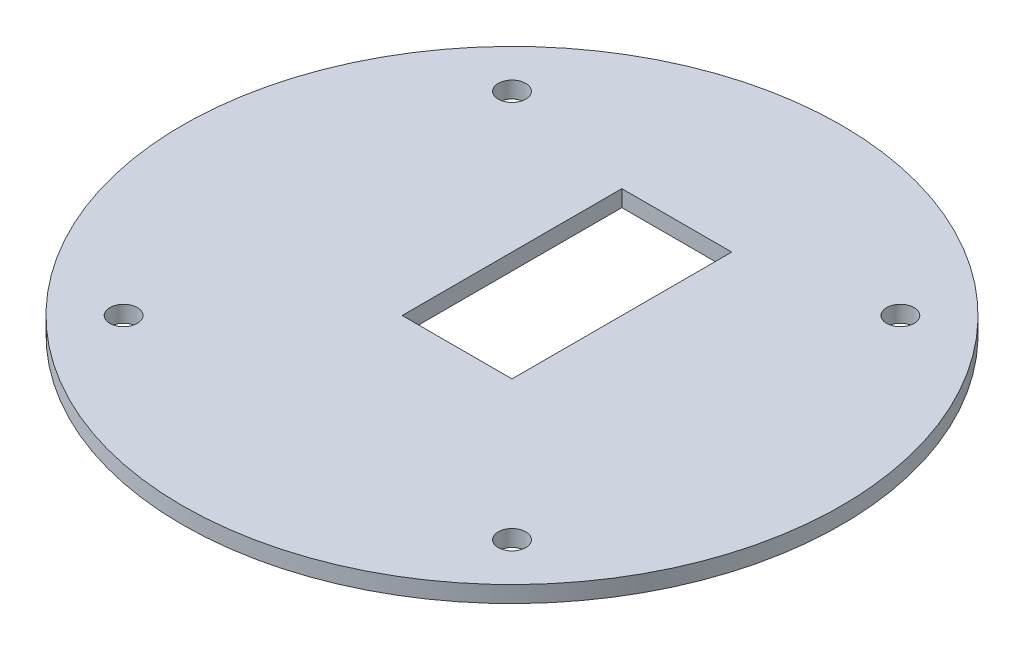
SolidWorks part; units mm, degrees
ref_plane "前视基准面" through (0, 0, 0) normal (0, 0, 1) x (1, 0, 0)
ref_plane "上视基准面" through (0, 0, 0) normal (0, 1, 0) x (1, 0, 0)
ref_plane "右视基准面" through (0, 0, 0) normal (1, 0, 0) x (0, 0, -1)
sketch "草图1" plane through (0, 0, 0) normal (0, 1, 0) x (1, 0, 0)
  line L0 (0, 0) -> (0, 72.3427) construction
  line L1 (10, 30) -> (-10, 30)
  line L2 (10, 30) -> (10, -10)
  line L3 (10, -10) -> (-10, -10)
  line L4 (-10, 30) -> (-10, -10)
  line L5 (10, 30) -> (-10, -10) construction
  line L6 (10, -10) -> (-10, 30) construction
  line L7 (-35.3553, 35.3553) -> (35.3553, 35.3553) construction
  circle A0 centre (0, 0) radius 60
  circle A1 centre (0, 0) radius 50 construction
  circle A2 centre (-35.3553, 35.3553) radius 2.5
  circle A3 centre (35.3553, 35.3553) radius 2.5
  circle A4 centre (35.3553, -35.3553) radius 2.5
  circle A5 centre (-35.3553, -35.3553) radius 2.5
  point P3 (0, 10)
  point P12 (0, 0)
  point P21 (0, 0)
  dimension "D1" = 120
  dimension "D5" = 100
  dimension "D6" = 5
  dimension "D2" = 40
  dimension "D3" = 10
  dimension "D4" = 20
  dimension "D7" = 4
extrude "凸台-拉伸1" add sketch "草图1" along normal blind 3
